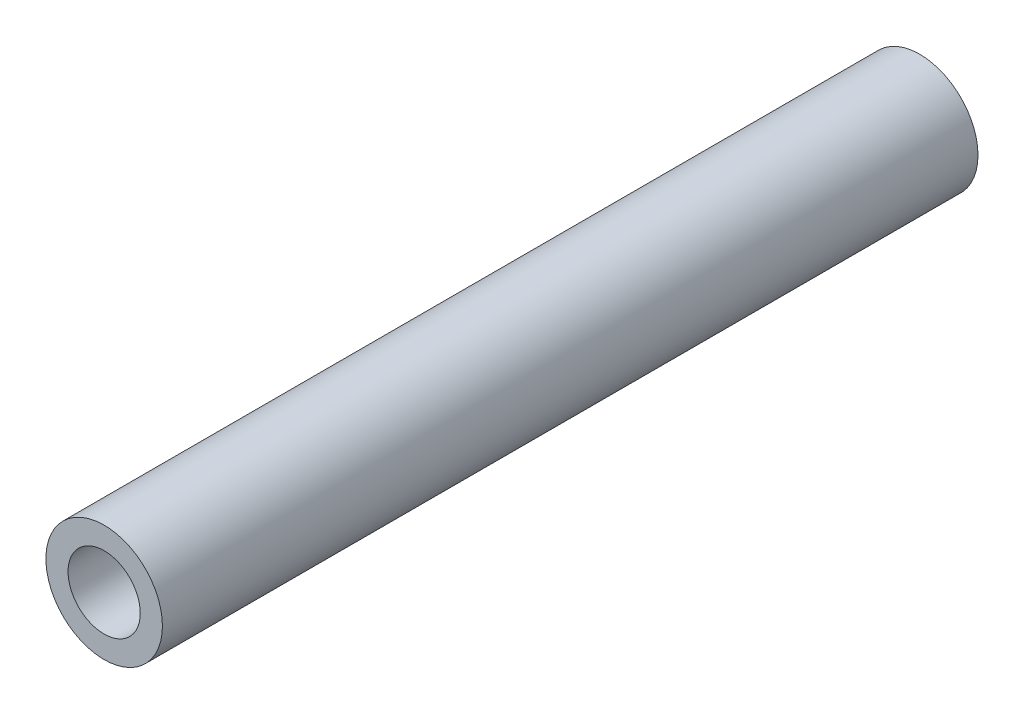
SolidWorks part; units mm, degrees
material "7050-T73510"
ref_plane "前视基准面" through (0, 0, 0) normal (0, 0, 1) x (1, 0, 0)
ref_plane "上视基准面" through (0, 0, 0) normal (0, 1, 0) x (1, 0, 0)
ref_plane "右视基准面" through (0, 0, 0) normal (1, 0, 0) x (0, 0, -1)
sketch "草图1" plane through (0, 0, 0) normal (0, 0, 1) x (1, 0, 0)
  circle A0 centre (0, 0) radius 2.5
  circle A1 centre (0, 0) radius 1.55
  dimension "D1" = 3.1
  dimension "D2" = 5
extrude "凸台-拉伸1" add sketch "草图1" along normal blind 35
